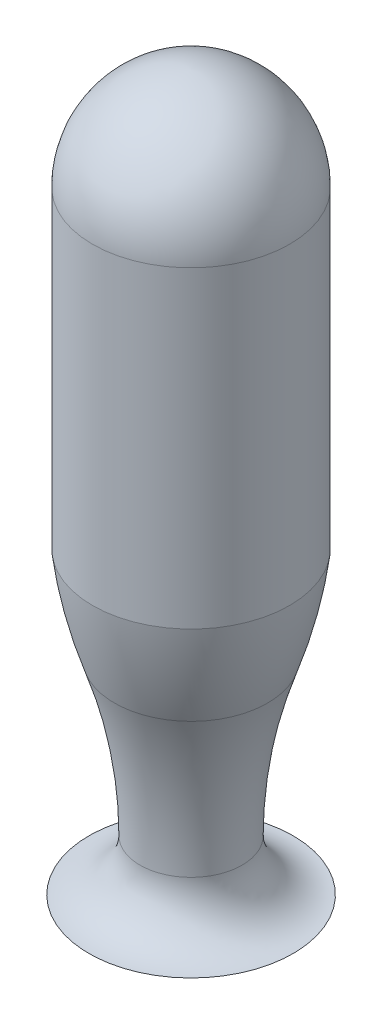
SolidWorks part; units mm, degrees
ref_plane "Alzado" through (0, 0, 0) normal (0, 0, 1) x (1, 0, 0)
ref_plane "Planta" through (0, 0, 0) normal (0, 1, 0) x (1, 0, 0)
ref_plane "Vista lateral" through (0, 0, 0) normal (1, 0, 0) x (0, 0, -1)
sketch "Croquis1" plane through (0, 0, 0) normal (0, 0, 1) x (1, 0, 0)
  line L0 (0, -5.8108) -> (0, 22.1868)
  line L1 (0, -5.8108) -> (4, -5.8108)
  line L3 (3.8617, 5.9314) -> (3.8617, 18.1892)
  arc A0 (4, -5.8108) -> (2, -3.8108) centre (4, -3.8108) cw
  arc A1 (2, -3.8108) -> (3, 2.1892) centre (20.5, -3.8108) cw
  arc A2 (3.8617, 18.1892) -> (0, 22.1868) centre (-0.1383, 18.1892) ccw
  arc A3 (3, 2.1892) -> (3.8617, 5.9314) centre (-14.5, 8.1892) ccw
  point P12 (3.5282, 4.0379)
  dimension "D2" = 18.5
  dimension "D5" = 4
  dimension "D6" = 2
  dimension "D7" = 10
  dimension "D8" = 2
  dimension "D1" = 4
  dimension "D3" = 18.5
  dimension "D4" = 24
  dimension "D9" = 12
  dimension "D10" = 27.9976
  dimension "D11" = 5.8108
revolve "Revolución1" add sketch "Croquis1" angle 360 about L0
sketch "Croquis2" plane through (0, -5.8108, 0) normal (0, -1, 0) x (1, 0, 0)
  circle A0 centre (0, 0) radius 1.5
  dimension "D1" = 3
extrude "Cortar-Extruir1" cut sketch "Croquis2" against normal blind 10
